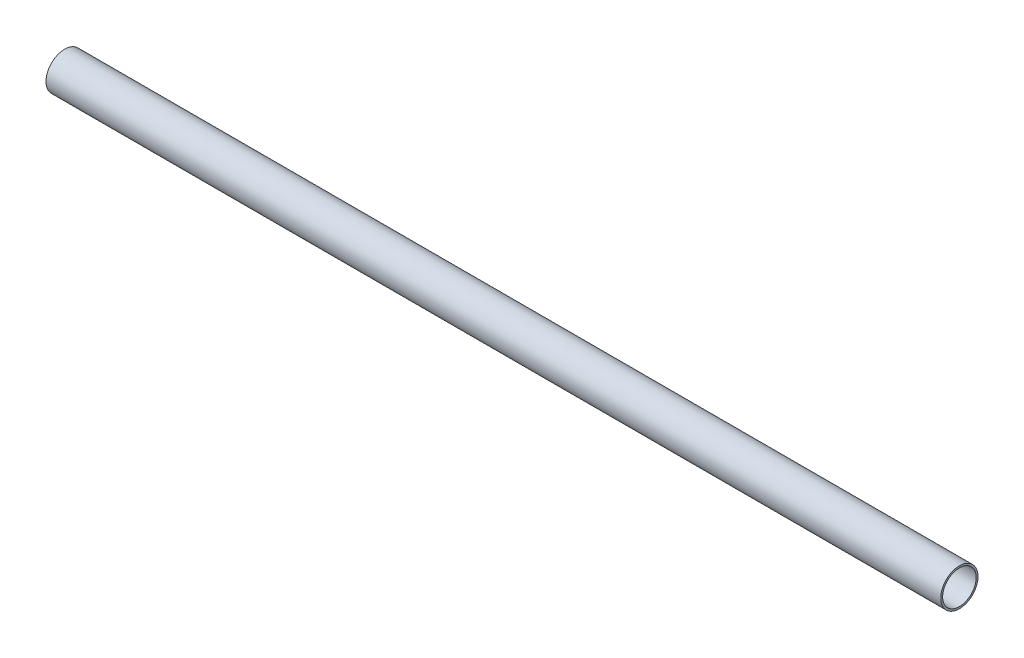
SolidWorks part; units mm, degrees
material "4140 Steel"
ref_plane "Front Plane" through (0, 0, 0) normal (0, 0, 1) x (1, 0, 0)
ref_plane "Top Plane" through (0, 0, 0) normal (0, 1, 0) x (1, 0, 0)
ref_plane "Right Plane" through (0, 0, 0) normal (1, 0, 0) x (0, 0, -1)
sketch "Sketch1" plane through (0, 0, 0) normal (1, 0, 0) x (0, 0, -1)
  circle A0 centre (0, 0) radius 12.7
extrude "Boss-Extrude1" add sketch "Sketch1" along normal blind 609.6
sketch "Sketch2" plane through (609.6, 0, 0) normal (1, 0, 0) x (0, 0, -1)
  circle A0 centre (0, 0) radius 11.43
extrude "Cut-Extrude1" cut sketch "Sketch2" against normal through all both and the other way through all
